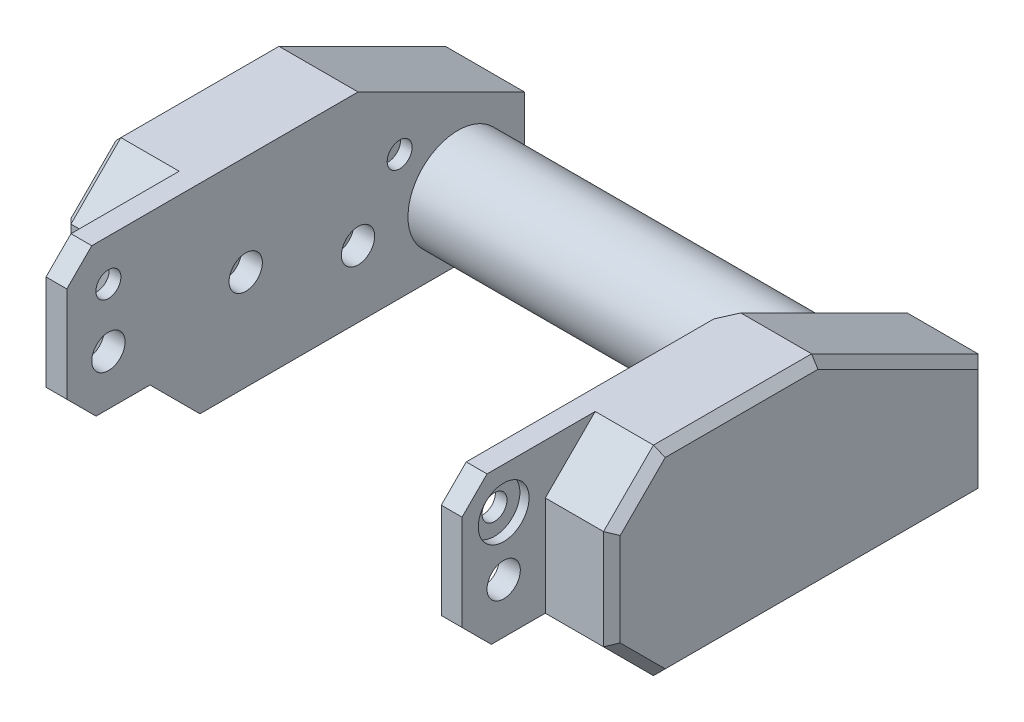
SolidWorks part; units mm, degrees
ref_plane "Front Plane" through (0, 0, 0) normal (0, 0, 1) x (1, 0, 0)
ref_plane "Top Plane" through (0, 0, 0) normal (0, 1, 0) x (1, 0, 0)
ref_plane "Right Plane" through (0, 0, 0) normal (1, 0, 0) x (0, 0, -1)
sketch "Sketch2" plane through (0, 0, 0) normal (1, 0, 0) x (0, 0, -1)
  line L1 (-22.5, -12) -> (22.5, -12)
  line L2 (-22.5, -12) -> (-22.5, 12)
  line L3 (-22.5, 12) -> (22.5, 12)
  line L4 (22.5, -12) -> (22.5, 12)
  line L5 (-22.5, -12) -> (22.5, 12) construction
  line L6 (-22.5, 12) -> (22.5, -12) construction
  point P0 (0, 0)
  dimension "D1" = 45
  dimension "D2" = 24
extrude "Boss-Extrude1" add sketch "Sketch2" along normal blind 50
sketch "Sketch14" plane through (50, 0, 0) normal (1, 0, 0) x (0, 0, -1)
  line L0 (2.5, 12) -> (22.5, 2)
  line L1 (22.5, 12) -> (-22.5, 12) construction
  line L2 (22.5, -12) -> (22.5, 12) construction
  line L5 (2.5, 12) -> (22.5, 12)
  line L6 (22.5, 12) -> (22.5, 2)
  dimension "D1" = 20
  dimension "D4" = 10
extrude "Cut-Extrude7" cut sketch "Sketch14" against normal up to surface (50 mm away) up to face at (0, 0, 0)
chamfer "Chamfer4" distance 6 angle 45 2 edges at (25, -12, 22.5) (25, 12, 22.5)
sketch "Sketch3" plane through (0, 0, -22.5) normal (0, 0, -1) x (-1, 0, 0)
  line L0 (0, 12) -> (-50, 12) construction
  line L1 (-47.5, -2) -> (-2.5, -2)
  line L2 (-47.5, -2) -> (-47.5, -12)
  line L3 (-47.5, -12) -> (-2.5, -12)
  line L4 (-2.5, -2) -> (-2.5, -12)
  line L5 (-50, -12) -> (0, -12) construction
  point P8 (-25, 12)
  point P9 (-25, -2)
  dimension "D1" = 45
  dimension "D3" = 10
extrude "Cut-Extrude1" cut sketch "Sketch3" against normal up to surface (45 mm away) up to face at (25, 0, 22.5)
sketch "Sketch4" plane through (2.5, 0, 0) normal (1, 0, 0) x (0, 0, -1)
  line L1 (22.5, -12) -> (22.5, 2) construction
  line L3 (-16.5, -12) -> (22.5, -12) construction
  circle A0 centre (14.5, -4) radius 2
  dimension "D1" = 8
  dimension "D2" = 8
  dimension "D3" = 4
extrude "Cut-Extrude2" cut sketch "Sketch4" along normal up to surface and the other way up to surface up to face at (50, 0.2857, 4.3571) other way up to face at (0, 0.2857, 4.3571)
sketch "Sketch8" plane through (0, 12, 0) normal (0, 1, 0) x (1, 0, 0)
  line L0 (0, 22.5) -> (50, 22.5) construction
  line L9 (2.5, 27.5) -> (47.5, 27.5)
  line L10 (2.5, 27.5) -> (2.5, -22.5)
  line L11 (2.5, -22.5) -> (47.5, -22.5)
  line L12 (47.5, 27.5) -> (47.5, -22.5)
  line L13 (50, -22.5) -> (0, -22.5) construction
  point P9 (25, 22.5)
  point P10 (25, 27.5)
  dimension "D1" = 45
  dimension "D3" = 50
extrude "Cut-Extrude4" cut sketch "Sketch8" against normal up to surface (14 mm away) up to face at (25, -2, -4.8333)
sketch "Sketch6" plane through (2.5, 0, 0) normal (1, 0, 0) x (0, 0, -1)
  circle A0 centre (14.5, -4) radius 6
  dimension "D1" = 12
extrude "Boss-Extrude2" add sketch "Sketch6" along normal up to surface (45 mm away)
sketch "Sketch7" plane through (0, 0, 0) normal (-1, 0, 0) x (0, 0, 1)
  line L0 (22.5, 6) -> (22.5, -6) construction
  line L1 (16.5, -12) -> (-22.5, -12) construction
  circle A0 centre (11, 0) radius 2
  dimension "D1" = 4
  dimension "D2" = 11.5
  dimension "D3" = 12
extrude "Cut-Extrude3" cut sketch "Sketch7" against normal up to surface (50 mm away)
sketch "Sketch13" plane through (47.5, 0, 0) normal (-1, 0, 0) x (0, 0, 1)
  line L0 (16.5, -12) -> (-22.5, -12) construction
  line L1 (-22.5, -12) -> (-22.5, 2) construction
  circle A0 centre (-2.5, -4) radius 2
  dimension "D3" = 4
  dimension "D1" = 8
  dimension "D2" = 20
extrude "Cut-Extrude6" cut sketch "Sketch13" along normal up to surface and the other way up to surface
sketch "Sketch29" plane through (0, 0, 0) normal (-1, 0, 0) x (0, 0, 1)
  line L0 (22.5, 6) -> (22.5, -6) construction
  line L1 (28.9853, 6) -> (22.5, 6)
  line L5 (22.5, -6) -> (28.9853, -6)
  line L6 (28.9853, -6) -> (32.5, -2.4853)
  line L7 (32.5, -2.4853) -> (32.5, 2.4853)
  line L8 (32.5, 2.4853) -> (28.9853, 6)
  line L9 (22.5, 6) -> (22.5, -6)
  line L11 (25.529, 7.5143) -> (21.4285, 3.4138) [skipped]
  line L12 (18.9857, -0.971) -> (21.036, -3.0213) [skipped]
  line L13 (20.5, 4.6268) -> (20.5, -1.1722) [skipped]
  arc A1 (22.5, -5.7446) -> (22.5, 5.7446) centre (26.5, 0) ccw construction
  dimension "D2" = 7
  dimension "D1" = 10
extrude "Boss-Extrude16" add sketch "Sketch29" against normal up to surface (50 mm away) up to face at (50, -4, -0.5)
sketch "Sketch30" plane through (0, 6, 0) normal (0, 1, 0) x (1, 0, 0)
  line L6 (50, -32.5) -> (0, -32.5) construction
  line L7 (2.5, -22.5) -> (47.5, -22.5)
  line L8 (2.5, -22.5) -> (2.5, -32.5)
  line L9 (2.5, -32.5) -> (47.5, -32.5)
  line L10 (47.5, -22.5) -> (47.5, -32.5)
  line L11 (47.5, -22.5) -> (47.5, -16.5) construction
  line L12 (2.5, 2.5) -> (2.5, -16.5) construction
  dimension "D1" = 22.5
extrude "Cut-Extrude13" cut sketch "Sketch30" against normal up to surface (12 mm away) up to face at (25, -6, 24.6618)
sketch "Sketch37" plane through (0, 0, 0) normal (-1, 0, 0) x (0, 0, 1)
  circle A0 centre (27.5, 0) radius 2
  dimension "D1" = 4
  dimension "D2" = 5
extrude "Cut-Extrude18" cut sketch "Sketch37" against normal up to surface (50 mm away)
sketch "Sketch43" plane through (50, 0, 0) normal (1, 0, 0) x (0, 0, -1)
  line L0 (22.5, -12) -> (22.5, 2) construction
  line L1 (-16.5, -12) -> (22.5, -12) construction
  circle A0 centre (7.5, 3) radius 1.5
  dimension "D1" = 15
  dimension "D2" = 3
  dimension "D3" = 15
extrude "Cut-Extrude20" cut sketch "Sketch43" against normal up to surface (50 mm away) up to face at (0, 0, 29.5)
sketch "Sketch44" plane through (50, 0, 0) normal (1, 0, 0) x (0, 0, -1)
  circle A0 centre (7.5, 3) radius 3.05
  dimension "D1" = 6.1
extrude "Cut-Extrude21" cut sketch "Sketch44" against normal blind 1.1
sketch "Sketch45" plane through (0, 0, 0) normal (-1, 0, 0) x (0, 0, 1)
  circle A0 centre (-7.5, 3) radius 3.05
  dimension "D1" = 6.1
extrude "Cut-Extrude22" cut sketch "Sketch45" against normal blind 1.1
sketch "Sketch48" plane through (50, 0, 0) normal (1, 0, 0) x (0, 0, -1)
  line L2 (-16.5, 12) -> (-22.5, 6)
  line L3 (-22.5, 6) -> (-28.9853, 6)
  line L4 (-28.9853, 6) -> (-32.5, 2.4853)
  line L5 (-32.5, 2.4853) -> (-32.5, 12)
  line L6 (-32.5, 12) -> (-16.5, 12)
extrude "Boss-Extrude23" add sketch "Sketch48" against normal up to surface (2.5 mm away) up to face at (47.5, 4.5, -7.5)
sketch "Sketch49" plane through (0, 0, 0) normal (-1, 0, 0) x (0, 0, 1)
  line L2 (28.9853, 6) -> (22.5, 6)
  line L3 (28.9853, 6) -> (22.5, 6) construction
  line L4 (22.5, 6) -> (16.5, 12) construction
  line L5 (22.5, 6) -> (16.5, 12)
  line L6 (16.5, 12) -> (32.5, 12)
  line L7 (32.5, 12) -> (32.5, 2.4853)
  line L8 (32.5, 2.4853) -> (28.9853, 6)
extrude "Boss-Extrude24" add sketch "Sketch49" against normal up to surface (2.5 mm away) up to face at (2.5, 1.5, -7.5)
sketch "Sketch55" plane through (0, 0, 0) normal (-1, 0, 0) x (0, 0, 1)
  line L0 (32.5, -2.4853) -> (32.5, 12) construction
  line L1 (-2.5, 12) -> (32.5, 12) construction
  circle A0 centre (27.5, 7) radius 3.05
  dimension "D1" = 5
  dimension "D2" = 5
  dimension "D3" = 6.1
extrude "Cut-Extrude28" cut sketch "Sketch55" against normal blind 1.1
sketch "Sketch57" plane through (0, 0, 0) normal (-1, 0, 0) x (0, 0, 1)
  circle A0 centre (27.5, 7) radius 1.5
  dimension "D1" = 3
extrude "Cut-Extrude29" cut sketch "Sketch57" against normal up to surface (50 mm away)
sketch "Sketch58" plane through (50, 0, 0) normal (1, 0, 0) x (0, 0, -1)
  circle A0 centre (-27.5, 7) radius 3.05
  dimension "D1" = 6.1
extrude "Cut-Extrude30" cut sketch "Sketch58" against normal blind 1.1
chamfer "Chamfer11" distance 3 angle 45 2 edges at (48.75, 12, 32.5) (1.25, 12, 32.5)
sketch "Sketch38" plane through (0, 0, 0) normal (-1, 0, 0) x (0, 0, 1)
  line L0 (-2.5, 12) -> (-22.5, 2)
  line L1 (-22.5, 2) -> (-22.5, -12)
  line L2 (-22.5, -12) -> (16.5, -12)
  line L3 (16.5, -12) -> (22.5, -6)
  line L4 (22.5, -6) -> (22.5, 6)
  line L6 (16.5, 12) -> (-2.5, 12)
  line L7 (16.5, 12) -> (22.5, 6)
  dimension "D1" = 12
extrude "Boss-Extrude19" add sketch "Sketch38" along normal blind 8
sketch "Sketch39" plane through (50, 0, 0) normal (1, 0, 0) x (0, 0, -1)
  line L0 (-22.5, 6) -> (-22.5, -6)
  line L1 (-22.5, -6) -> (-16.5, -12)
  line L2 (-16.5, -12) -> (22.5, -12)
  line L3 (22.5, -12) -> (22.5, 2)
  line L4 (22.5, 2) -> (2.5, 12)
  line L5 (2.5, 12) -> (-16.5, 12)
  line L6 (-16.5, 12) -> (-22.5, 6)
  dimension "D1" = 12
extrude "Boss-Extrude20" add sketch "Sketch39" along normal blind 8
chamfer "Chamfer7" distance 1 angle 45 14 edges at (58, 12, 7) (58, 7, -12.5) (58, -5, -22.5) (58, -12, -3) (58, -9, 19.5) (58, 0, 22.5) (58, 9, 19.5) (-8, 9, 19.5) (-8, 0, 22.5) (-8, -9, 19.5) (-8, -12, -3) (-8, -5, -22.5) (-8, 7, -12.5) (-8, 12, 7)
chamfer "Chamfer8" distance 1 angle 45 4 edges at (47.5, 7, -12.5) (47.5, -9, 19.5) (47.5, -12, -3) (47.5, -5, -22.5)
chamfer "Chamfer9" [suppressed] distance 1 angle 45
